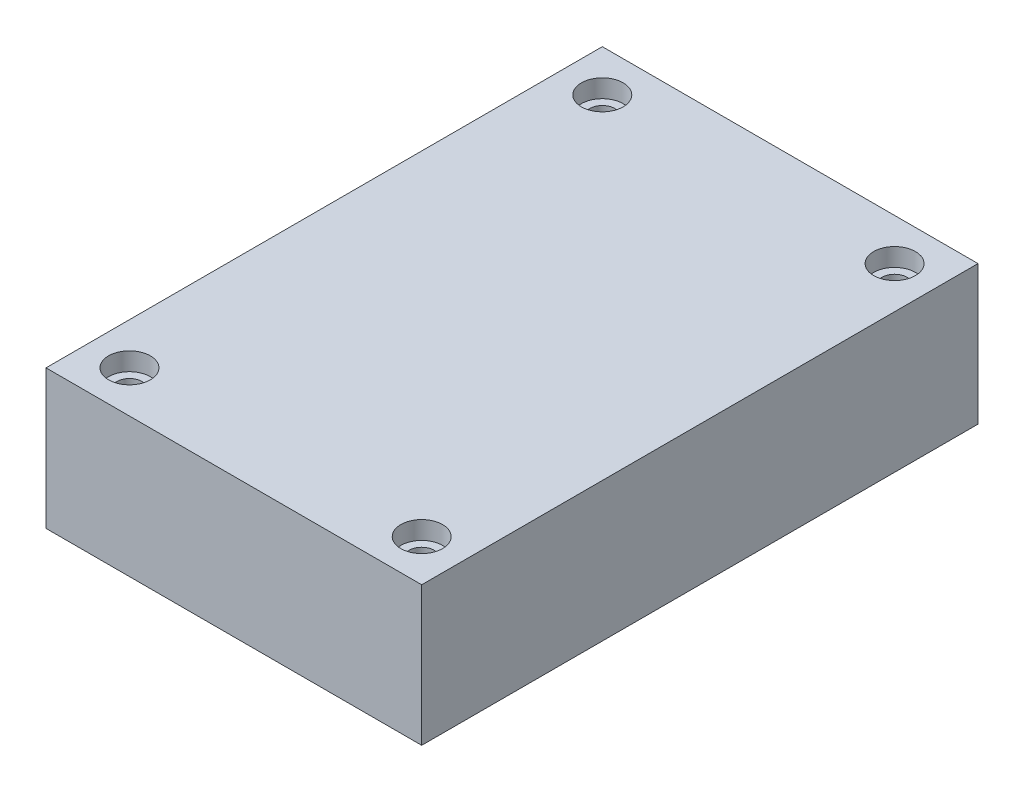
SolidWorks part; units mm, degrees
ref_plane "Ebene vorne" through (0, 0, 0) normal (0, 0, 1) x (1, 0, 0)
ref_plane "Ebene oben" through (0, 0, 0) normal (0, 1, 0) x (1, 0, 0)
ref_plane "Ebene rechts" through (0, 0, 0) normal (1, 0, 0) x (0, 0, -1)
sketch "Skizze1" plane through (0, 0, 0) normal (0, 0, 1) x (1, 0, 0)
  line L1 (67.5347, -25) -> (-67.5347, -25)
  line L2 (67.5347, -25) -> (67.5347, 25)
  line L3 (67.5347, 25) -> (-67.5347, 25)
  line L4 (-67.5347, -25) -> (-67.5347, 25)
  line L5 (67.5347, -25) -> (-67.5347, 25) construction
  line L6 (67.5347, 25) -> (-67.5347, -25) construction
  point P0 (0, 0)
  dimension "D1" = 50
  dimension "D2" = 135.0694
extrude "Aufsatz-Linear austragen1" add sketch "Skizze1" along normal blind 200 contours L4 L3 L2 L1
ref_plane "Ebene1" through (0, 0, 100) normal (0, 0, 1) x (1, 0, 0)
sketch "Skizze3" plane through (0, 25, 0) normal (0, 1, 0) x (1, 0, 0)
  line L0 (-67.5347, -200) -> (-67.5347, 0) construction
  line L1 (67.5347, -200) -> (67.5347, 0) construction
  line L2 (-27.5, -100) -> (27.5, -100) construction
  circle A0 centre (0, -150) radius 67.5347
  dimension "D1" = 50
hole_wizard "Stirnsenkung für M8 Senkschraube (Kopf Button)4" positions "Skizze9" profile "Skizze10" counterbore size "M8" standard "ANSI Metrisch" end condition through all
sketch "Skizze9" plane through (0, 25, 0) normal (0, 1, 0) x (1, 0, 0)
  line L1 (67.5347, -200) -> (-67.5347, -200) construction
  line L2 (-67.5347, -200) -> (-67.5347, 0) construction
  circle A0 centre (-52.5347, -185) radius 15
  point P1 (-52.5347, -185)
  dimension "D1" = 30
sketch "Skizze10" plane through (-52.5347, 25, 185) normal (1, 0, 0) x (0, 0, 1)
  line L0 (0, 0) -> (0, 50)
  line L1 (0, 50) -> (4.5, 50)
  line L3 (4.5, 50) -> (4.5, 6.5)
  line L4 (4.5, 6.5) -> (7.5, 6.5)
  line L5 (7.5, 6.5) -> (7.5, 0)
  line L7 (7.5, 0) -> (0, 0)
  line L11 (0, -6.35) -> (0, 107.95) construction
  dimension "Bohrerdurchmesser" = 9
  dimension "Bohrungstiefe" = 50
  dimension "Senkdurchmesser2" = 15
  dimension "Senktiefe2" = 6.5
mirror "Spiegeln2" about plane through (0, 0, 0) normal (1, 0, 0) of "Stirnsenkung für M8 Senkschraube (Kopf Button)4"
mirror "Spiegeln3" about plane through (0, 0, 100) normal (0, 0, 1) of "Spiegeln2", "Stirnsenkung für M8 Senkschraube (Kopf Button)4"
